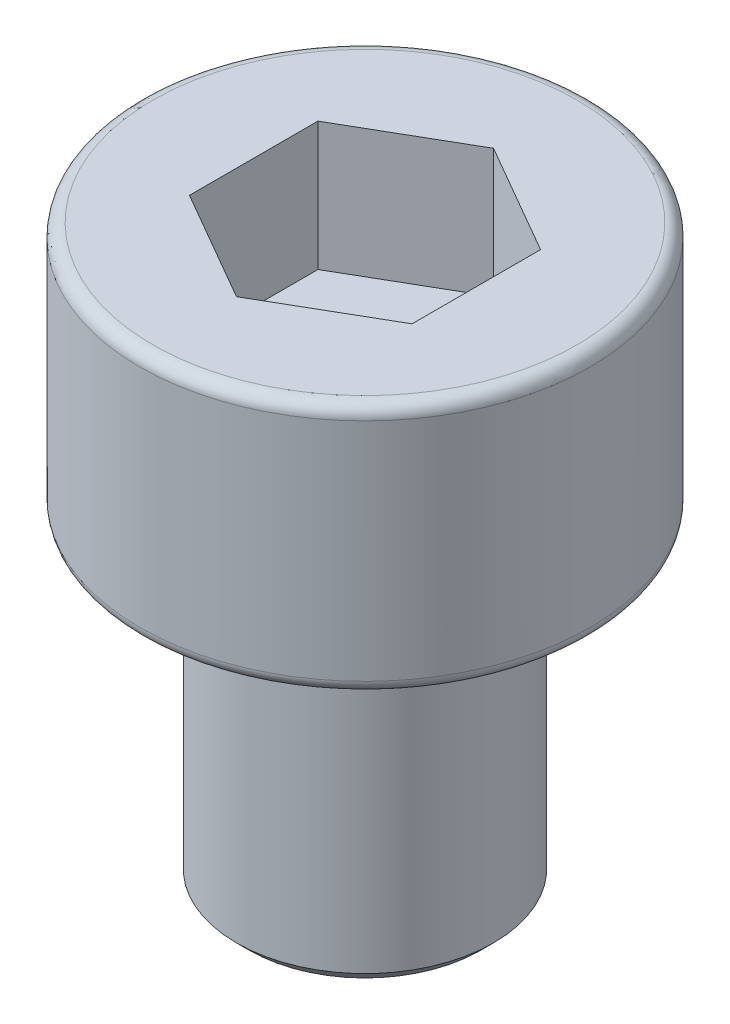
SolidWorks part; units mm, degrees
material "不锈钢 (铁素体)"
ref_plane "前视基准面" through (0, 0, 0) normal (0, 0, 1) x (1, 0, 0)
ref_plane "上视基准面" through (0, 0, 0) normal (0, 1, 0) x (1, 0, 0)
ref_plane "右视基准面" through (0, 0, 0) normal (1, 0, 0) x (0, 0, -1)
sketch "草图1" plane through (0, 0, 0) normal (0, 0, 1) x (1, 0, 0)
  line L0 (0, 0) -> (0, -21.235) construction
  line L1 (0, 0) -> (3.5, 0)
  line L2 (3.5, 0) -> (3.5, -3.91)
  line L3 (3.5, -3.91) -> (2, -3.91)
  line L4 (2, -3.91) -> (2, -8.91)
  line L5 (2, -8.91) -> (0, -8.91)
  line L6 (0, -8.91) -> (0, 0)
  point P5 (2.75, -3.91)
  dimension "D1" = 3.91
  dimension "D2" = 7
  dimension "D3" = 4
  dimension "D4" = 5
revolve "旋转1" add sketch "草图1" angle 360 about L0
cosmetic thread "装饰螺纹线1" parameters "D2"=2.459
sketch "草图2" plane through (0, 0, 0) normal (0, 1, 0) x (1, 0, 0)
  line L1 (0, 2) -> (-1.7321, 1)
  line L2 (-1.7321, 1) -> (-1.7321, -1)
  line L3 (-1.7321, -1) -> (0, -2)
  line L4 (0, -2) -> (1.7321, -1)
  line L5 (1.7321, -1) -> (1.7321, 1)
  line L6 (1.7321, 1) -> (0, 2)
  circle A0 centre (0, 0) radius 2 construction
  dimension "D1" = 4
extrude "切除-拉伸1" cut sketch "草图2" against normal blind 2
fillet "圆角1" radius 0.2 2 edges at (0, 0, 3.5) (0, -3.91, 3.5)
chamfer "倒角1" distance 0.2 angle 45 1 edges at (0, -8.91, 2)
